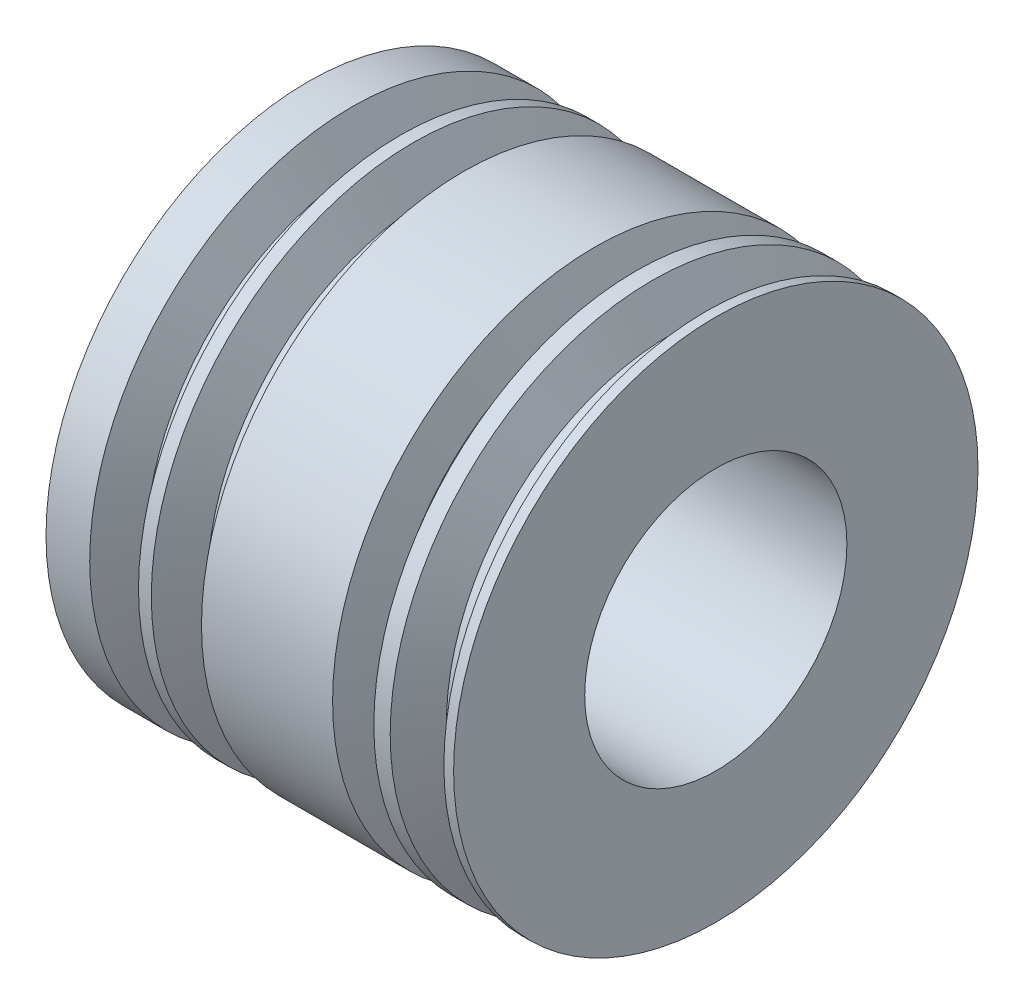
SolidWorks part; units mm, degrees
ref_plane "Płaszczyzna przednia" through (0, 0, 0) normal (0, 0, 1) x (1, 0, 0)
ref_plane "Płaszczyzna górna" through (0, 0, 0) normal (0, 1, 0) x (1, 0, 0)
ref_plane "Płaszczyzna prawa" through (0, 0, 0) normal (1, 0, 0) x (0, 0, -1)
sketch "Szkic1" plane through (0, 0, 0) normal (0, 0, 1) x (1, 0, 0)
  line L0 (0, 0) -> (-9, 0)
  line L1 (-9, 0) -> (-9, 3)
  line L2 (-9, 3) -> (-8, 3)
  line L3 (-8, 3) -> (-7.5864, 2.1326)
  line L4 (-7.5864, 2.1326) -> (-7.3637, 2.1326)
  line L5 (-7.3637, 2.1326) -> (-6.8837, 3)
  line L6 (-6.8837, 3) -> (-6.59, 3)
  line L7 (-6.59, 3) -> (-6.1764, 2.1326)
  line L11 (-0.1776, 2.1326) -> (0.1049, 3)
  line L12 (0.1049, 3) -> (0.3276, 3)
  line L13 (0.3276, 3) -> (0.3276, 0)
  line L14 (0.3276, 0) -> (0, 0)
  line L15 (0.3276, -3) -> (-3.999, -3)
  line L16 (-6.1764, 2.1326) -> (-5.9079, 2.1326)
  line L17 (-5.9079, 2.1326) -> (-5.4418, 3)
  line L18 (-0.1776, 2.1326) -> (-0.7042, 2.1326)
  line L19 (-0.7042, 2.1326) -> (-1.1236, 3)
  line L20 (-1.1236, 3) -> (-1.4981, 3)
  line L21 (-1.4981, 3) -> (-1.8108, 2.1326)
  line L22 (-1.8108, 2.1326) -> (-2.1272, 2.1326)
  line L23 (-2.1272, 2.1326) -> (-2.4418, 3)
  line L24 (-2.4418, 3) -> (-5.4418, 3)
  dimension "D1" = 3
  dimension "D2" = 3
  dimension "D3" = 9
  dimension "D4" = 1
  dimension "D5" = 3
revolve "Obrót1" add sketch "Szkic1" angle 360 about L15
